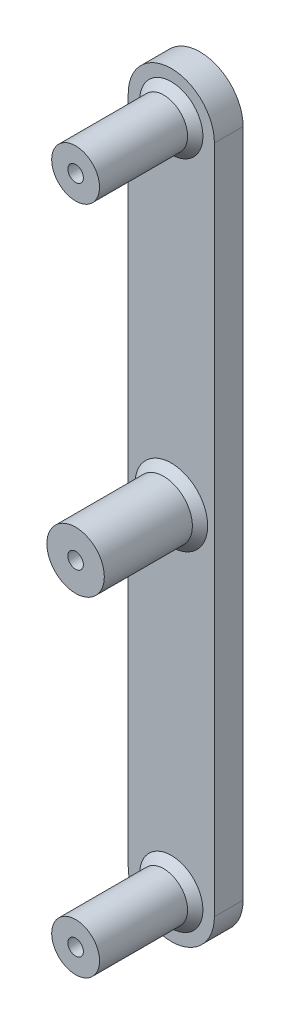
SolidWorks part; units mm, degrees
ref_plane "Front Plane" through (0, 0, 0) normal (1, 0, 0) x (0, 1, 0)
ref_plane "Top Plane" through (0, 0, 0) normal (0, 0, 1) x (0, 1, 0)
ref_plane "Right Plane" through (0, 0, 0) normal (0, 1, 0) x (-1, 0, 0)
sketch "Sketch1" plane through (0, 0, 0) normal (0, 0, 1) x (0, 1, 0)
  line L0 (-35, 0) -> (35, 0) construction
  line L1 (-35, 2.5) -> (35, 2.5)
  line L2 (-35, -2.5) -> (35, -2.5)
  arc A0 (-35, 2.5) -> (-35, -2.5) centre (-35, 0) ccw
  arc A1 (35, -2.5) -> (35, 2.5) centre (35, 0) ccw
  circle A2 centre (-35, 0) radius 2.5
  circle A3 centre (35, 0) radius 2.5
  point P2 (0, 0)
  dimension "D1" = 5
  dimension "D2" = 70
extrude "Boss-Extrude1" add sketch "Sketch1" along normal blind 10
sketch "Sketch2" plane through (0, 0, 0) normal (0, 0, -1) x (1, 0, 0)
  line L0 (0, 35) -> (0, -35) construction
  line L1 (4.5, 35) -> (4.5, -35)
  line L2 (-4.5, 35) -> (-4.5, -35)
  arc A0 (4.5, 35) -> (-4.5, 35) centre (0, 35) ccw
  arc A1 (-4.5, -35) -> (4.5, -35) centre (0, -35) ccw
  circle A2 centre (0, -35) radius 2.5 construction
  point P4 (0, 0)
  dimension "D1" = 2
extrude "Boss-Extrude2" add sketch "Sketch2" along normal blind 3
sketch "Sketch3" plane through (0, 0, 10) normal (0, 0, 1) x (1, 0, 0)
  circle A0 centre (0, -35) radius 0.8125
  circle A1 centre (0, 35) radius 0.8125
  dimension "D1" = 1.625
extrude "Cut-Extrude1" cut sketch "Sketch3" against normal blind 20
chamfer "Chamfer1" distance 0.8 angle 45 2 edges at (-2.5, 35, 0) (2.5, -35, 0)
sketch "Sketch4" plane through (0, 0, 0) normal (0, 0, 1) x (1, 0, 0)
  circle A0 centre (0, 0) radius 3
  dimension "D1" = 6
extrude "Boss-Extrude3" add sketch "Sketch4" along normal up to surface (10 mm away) up to face at (0.8125, -35, 10)
chamfer "Chamfer2" distance 0.8 angle 45 1 edges at (-3, 0, 0)
sketch "Sketch5" plane through (0, 0, 10) normal (0, 0, 1) x (1, 0, 0)
  circle A0 centre (0, 0) radius 0.8125
  dimension "D1" = 1.625
extrude "Cut-Extrude2" cut sketch "Sketch5" against normal blind 20
